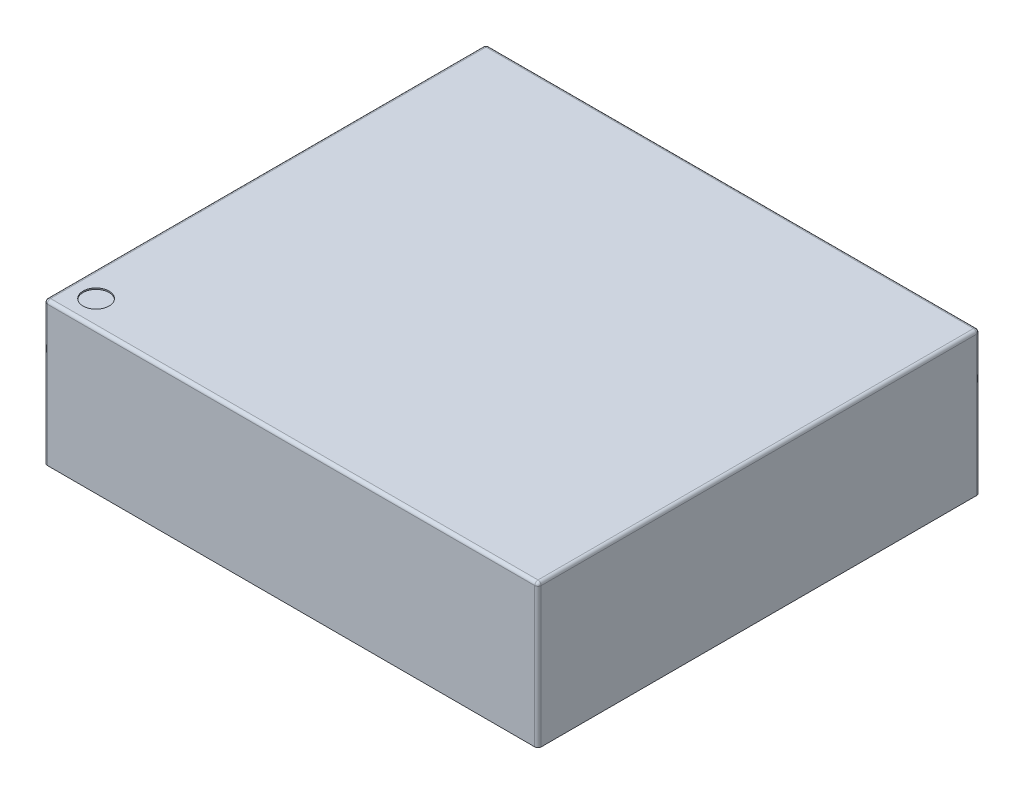
SolidWorks part; units mm, degrees
ref_plane "Front Plane" through (0, 0, 0) normal (0, 0, 1) x (1, 0, 0)
ref_plane "Top Plane" through (0, 0, 0) normal (0, 1, 0) x (1, 0, 0)
ref_plane "Right Plane" through (0, 0, 0) normal (1, 0, 0) x (0, 0, -1)
sketch "Sketch1" plane through (0, 0, 0) normal (0, 1, 0) x (1, 0, 0)
  line L1 (-0.95, -0.85) -> (0.95, -0.85)
  line L2 (-0.95, -0.85) -> (-0.95, 0.85)
  line L3 (-0.95, 0.85) -> (0.95, 0.85)
  line L4 (0.95, -0.85) -> (0.95, 0.85)
  line L5 (-0.95, -0.85) -> (0.95, 0.85) construction
  line L6 (-0.95, 0.85) -> (0.95, -0.85) construction
  point P0 (0, 0)
  dimension "D1" = 0.95
  dimension "D2" = 0.85
extrude "Boss-Extrude1" add sketch "Sketch1" along normal blind 0.55
sketch "Sketch2" plane through (0, 0.55, 0) normal (0, 1, 0) x (1, 0, 0)
  line L0 (0.95, -0.85) -> (0.95, 0.85) construction
  line L5 (0.95, 0.85) -> (-0.95, 0.85) construction
  circle A0 centre (-0.85, -0.75) radius 0.05
  dimension "D3" = 1.6
  dimension "D1" = 0.1
  dimension "D2" = 1.8
extrude "Cut-Extrude1" cut sketch "Sketch2" against normal blind 0.005 contours A0
sketch "Sketch3" plane through (0, 0, 0) normal (0, -1, 0) x (1, 0, 0)
  line L1 (-0.1, 0.7738) -> (0.1, 0.7738)
  line L2 (0.1, -0.3738) -> (0.1, -0.4738)
  line L3 (0, -0.3738) -> (0.1, -0.3738)
  line L4 (-0.6, 0.3738) -> (-0.5, 0.3738)
  line L5 (-0.6, 0.3738) -> (-0.6, 0.7738)
  line L6 (-0.6, 0.7738) -> (-0.4, 0.7738)
  line L7 (-0.4, 0.4738) -> (-0.4, 0.7738)
  line L8 (0.1, -0.4738) -> (0.1, -0.7738)
  line L9 (-0.4, 0.4738) -> (-0.5, 0.3738)
  line L10 (-0.1, 0.3738) -> (-0.1, 0.7738)
  line L11 (0, 0.3738) -> (-0.1, 0.3738)
  line L12 (0.1, 0.4738) -> (0.1, 0.7738)
  line L13 (0, 0.3738) -> (0.1, 0.3738)
  line L14 (0.1, 0.3738) -> (0.1, 0.4738)
  line L15 (0, -0.3738) -> (-0.1, -0.3738)
  line L16 (-0.1, -0.3738) -> (-0.1, -0.7738)
  line L17 (-0.1, -0.7738) -> (0.1, -0.7738)
  line L19 (0.95, 0.85) -> (0.95, -0.85) construction
  line L20 (-0.95, 0.85) -> (0.95, 0.85) construction
  line L21 (-0.6, -0.7738) -> (-0.4, -0.7738)
  line L22 (-0.4, -0.3738) -> (-0.4, -0.4738)
  line L23 (-0.5, -0.3738) -> (-0.4, -0.3738)
  line L24 (-0.5, -0.3738) -> (-0.6, -0.3738)
  line L25 (-0.4, -0.4738) -> (-0.4, -0.7738)
  line L26 (-0.6, -0.3738) -> (-0.6, -0.7738)
  line L27 (0.6, -0.3738) -> (0.6, -0.7738)
  line L28 (0.4, -0.4738) -> (0.4, -0.7738)
  line L29 (0.5, -0.3738) -> (0.6, -0.3738)
  line L30 (0.5, -0.3738) -> (0.4, -0.3738)
  line L31 (0.4, -0.3738) -> (0.4, -0.4738)
  line L32 (0.6, -0.7738) -> (0.4, -0.7738)
  dimension "D1" = 0.35
  dimension "D2" = 0.45
  dimension "D3" = 0.85
  dimension "D4" = 1.35
  dimension "D5" = 0.0762
  dimension "D6" = 1.2238
extrude "Boss-Extrude2" add sketch "Sketch3" along normal blind 0.018 contours L9 L7 L6 L5 L4 | L13 L14 L12 L1 L10 L11 | L24 L26 L21 L25 L22 L23 | L16 L17 L8 L2 L3 L15 | L32 L27 L29 L30 L31 L28
fillet "Fillet1" radius 0.0125 8 edges at (0, 0.55, -0.85) (0.95, 0.55, 0) (0, 0.55, 0.85) (-0.95, 0.55, 0) (-0.95, 0.275, 0.85) (-0.95, 0.275, -0.85) (0.95, 0.275, -0.85) (0.95, 0.275, 0.85)
